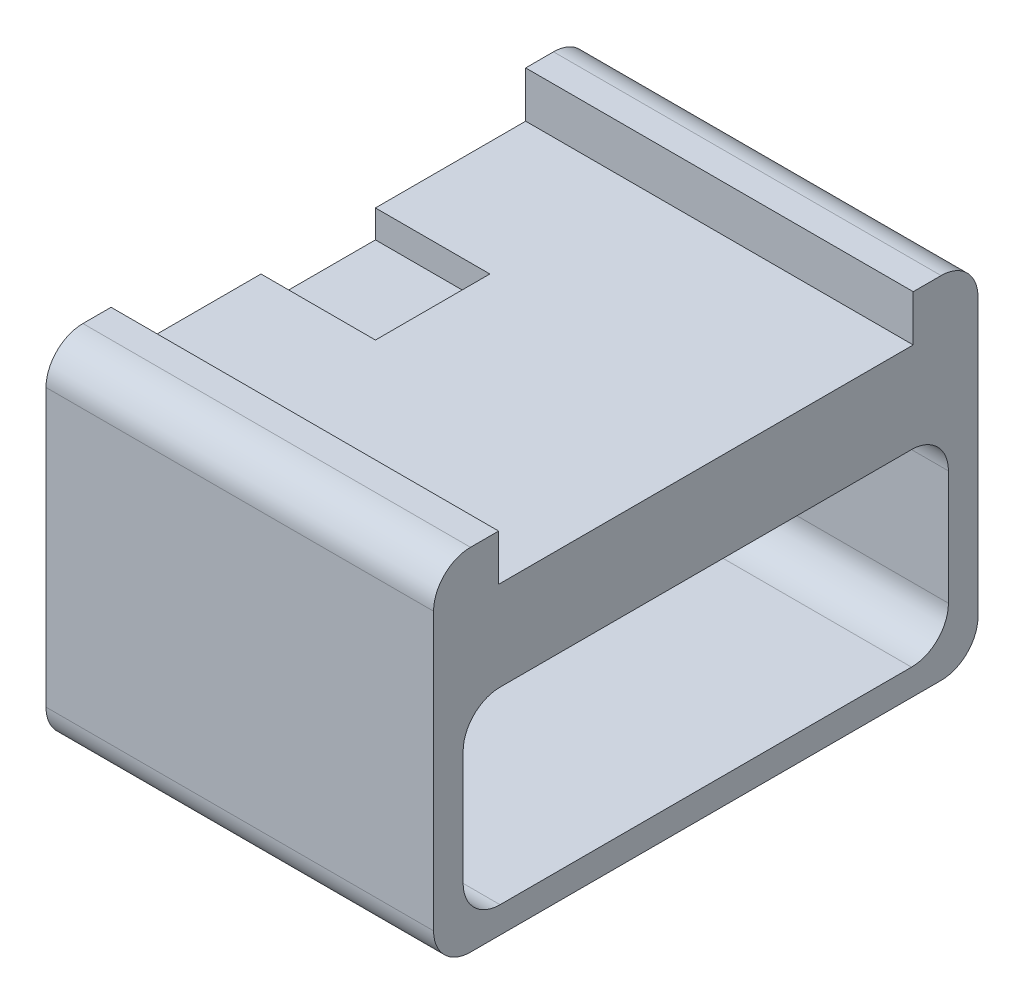
SolidWorks part; units mm, degrees
ref_plane "Front Plane" through (0, 0, 0) normal (0, 0, 1) x (1, 0, 0)
ref_plane "Top Plane" through (0, 0, 0) normal (0, 1, 0) x (1, 0, 0)
ref_plane "Right Plane" through (0, 0, 0) normal (1, 0, 0) x (0, 0, -1)
sketch "Sketch3" plane through (0, 0, 0) normal (1, 0, 0) x (0, 0, -1)
  line L0 (-12.75, -9.5) -> (12.75, -9.5)
  line L1 (-14.75, -7.5) -> (-14.75, 7.5)
  line L2 (-12.75, 9.5) -> (12.75, 9.5)
  line L3 (14.75, -7.5) -> (14.75, 7.5)
  line L4 (0, 9.5) -> (0, -9.5) construction
  line L5 (14.75, 0) -> (-14.75, 0) construction
  arc A0 (14.75, -7.5) -> (12.75, -9.5) centre (12.75, -7.5) cw
  arc A1 (-14.75, -7.5) -> (-12.75, -9.5) centre (-12.75, -7.5) ccw
  arc A2 (-12.75, 9.5) -> (-14.75, 7.5) centre (-12.75, 7.5) ccw
  arc A3 (12.75, 9.5) -> (14.75, 7.5) centre (12.75, 7.5) cw
  point P16 (0, 0)
  dimension "D3" = 2
  dimension "D1" = 19
  dimension "D2" = 25.5
extrude "Boss-Extrude1" add sketch "Sketch3" along normal blind 21
sketch "Sketch5" plane through (0, 9.5, 0) normal (0, 1, 0) x (1, 0, 0)
  line L0 (0, 12.75) -> (0, -12.75) construction
  line L1 (6.2, 3.1) -> (0, 3.1)
  line L2 (6.2, 3.1) -> (6.2, -3.1)
  line L3 (6.2, -3.1) -> (0, -3.1)
  line L4 (0, 3.1) -> (0, -3.1)
  line L5 (6.2, 0) -> (0, 0) construction
  dimension "D1" = 6.2
  dimension "D2" = 6.2
extrude "Cut-Extrude1" cut sketch "Sketch5" against normal blind 4
sketch "Sketch7" plane through (0, 0, 0) normal (-1, 0, 0) x (0, 0, 1)
  line L0 (0, 2.1353) -> (0, -8.0729) construction
  line L1 (-11.1476, -8.0729) -> (11.1476, -8.0729)
  line L2 (-13.1476, -6.0729) -> (-13.1476, 0.1353)
  line L3 (-11.1476, 2.1353) -> (11.1476, 2.1353)
  line L4 (13.1476, -6.0729) -> (13.1476, 0.1353)
  line L5 (12.75, -9.5) -> (-12.75, -9.5) construction
  arc A0 (11.1476, -8.0729) -> (13.1476, -6.0729) centre (11.1476, -6.0729) ccw
  arc A1 (11.1476, 2.1353) -> (13.1476, 0.1353) centre (11.1476, 0.1353) cw
  arc A2 (-13.1476, 0.1353) -> (-11.1476, 2.1353) centre (-11.1476, 0.1353) cw
  arc A3 (-13.1476, -6.0729) -> (-11.1476, -8.0729) centre (-11.1476, -6.0729) ccw
  point P6 (0, -2.9688)
  point P7 (0, -9.5)
  dimension "D1" = 2
extrude "Cut-Extrude2" cut sketch "Sketch7" against normal through all both and the other way through all
sketch "Sketch9" plane through (0, 9.5, 0) normal (0, 1, 0) x (1, 0, 0)
  line L0 (0, 12.75) -> (0, 3.1) construction
  line L1 (0, 11.24) -> (24.2849, 11.24)
  line L2 (0, 11.24) -> (0, -11.2248)
  line L3 (0, -11.2248) -> (24.2849, -11.2248)
  line L4 (24.2849, 11.24) -> (24.2849, -11.2248)
  line L5 (24.2849, 0.0076) -> (0, 0.0076) construction
  line L6 (6.2, -3.1) -> (6.2, 3.1) construction
  point P8 (6.2, 0)
  point P12 (6.2, -0.2283)
extrude "Cut-Extrude3" cut sketch "Sketch9" against normal blind 2.5
sketch "Sketch10" plane through (21, 0, 0) normal (1, 0, 0) x (0, 0, -1)
  line L1 (-15.9191, 11.2845) -> (15.8968, 11.2845)
  line L2 (-15.9191, 11.2845) -> (-15.9191, -10.3889)
  line L3 (-15.9191, -10.3889) -> (15.8968, -10.3889)
  line L4 (15.8968, 11.2845) -> (15.8968, -10.3889)
